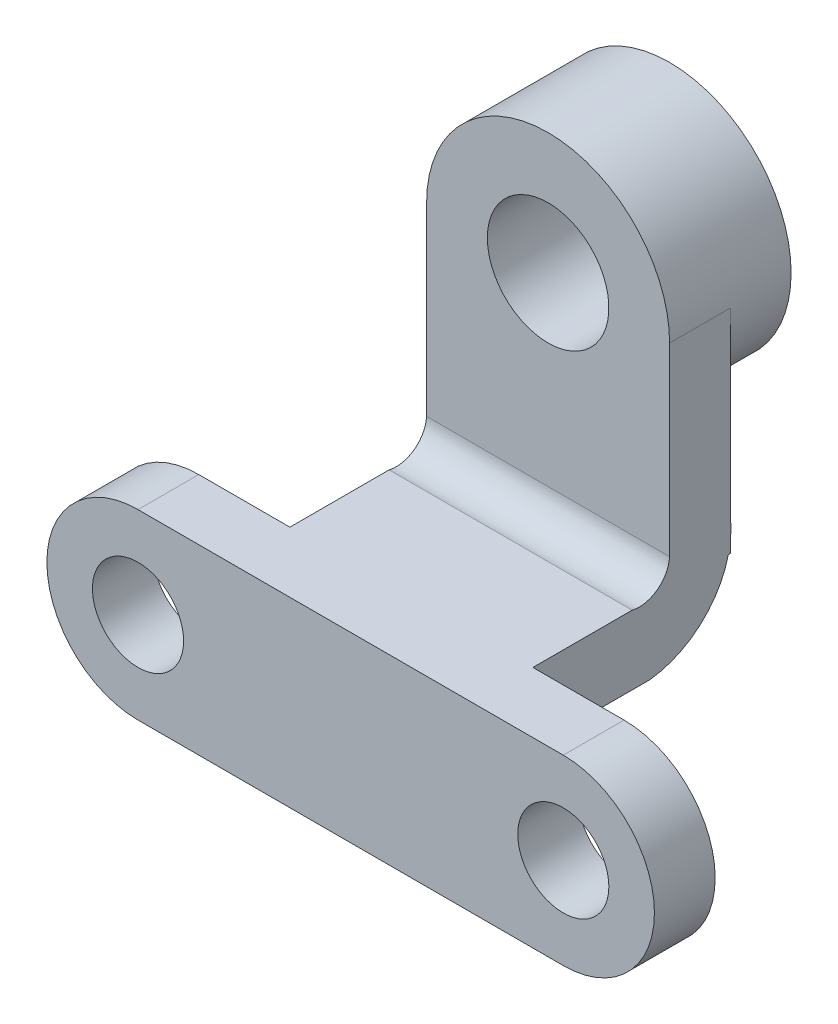
SolidWorks part; units mm, degrees
ref_plane "Front Plane" through (0, 0, 0) normal (0, 0, 1) x (1, 0, 0)
ref_plane "Top Plane" through (0, 0, 0) normal (0, 1, 0) x (1, 0, 0)
ref_plane "Right Plane" through (0, 0, 0) normal (1, 0, 0) x (0, 0, -1)
sketch "Sketch1" plane through (0, 0, 0) normal (0, 0, 1) x (1, 0, 0)
  line L0 (-78.5091, 0) -> (99.2909, 0) construction
  line L1 (-78.5091, 38.1) -> (99.2909, 38.1)
  line L2 (-78.5091, -38.1) -> (99.2909, -38.1)
  arc A0 (-78.5091, 38.1) -> (-78.5091, -38.1) centre (-78.5091, 0) ccw
  arc A1 (99.2909, -38.1) -> (99.2909, 38.1) centre (99.2909, 0) ccw
  circle A2 centre (-78.5091, 0) radius 19.05
  circle A3 centre (99.2909, 0) radius 19.05
  point P3 (10.3909, 0)
  dimension "D1" = 38.1
  dimension "D3" = 38.1
  dimension "D4" = 38.1
  dimension "D2" = 177.8
extrude "Boss-Extrude1" add sketch "Sketch1" against normal blind 25.4
ref_plane "Plane1" through (0, 0, -82.55) normal (0, 0, -1) x (-1, 0, 0)
sketch "Sketch3" plane through (0, 0, -82.55) normal (0, 0, -1) x (-1, 0, 0)
  line L0 (-61.1909, 127) -> (-61.1909, 38.1)
  line L1 (-99.2909, 38.1) -> (78.5091, 38.1) construction
  line L2 (40.4091, 127) -> (40.4091, 38.1)
  line L3 (40.4091, 38.1) -> (-61.1909, 38.1)
  arc A0 (40.4091, 127) -> (-61.1909, 127) centre (-10.3909, 127) ccw
  circle A1 centre (-10.3909, 127) radius 25.4
  circle A2 centre (78.5091, 0) radius 19.05 construction
  dimension "D1" = 101.6
  dimension "D2" = 50.8
  dimension "D3" = 127
extrude "Boss-Extrude2" add sketch "Sketch3" along normal blind 25.4 separate body
sketch "Sketch4" plane through (0, 0, -107.95) normal (0, 0, -1) x (-1, 0, 0)
  circle A0 centre (-10.3909, 127) radius 50.8
  circle A1 centre (-10.3909, 127) radius 25.4
extrude "Boss-Extrude3" add sketch "Sketch4" along normal blind 25.4
sketch "Sketch5" plane through (0, 38.1, 0) normal (0, 1, 0) x (1, 0, 0)
  line L0 (-40.1917, 82.55) -> (61.1909, 82.55)
  line L1 (41.91, 82.55) -> (-41.91, 82.55) construction
  line L2 (-40.4091, 82.55) -> (61.1909, 82.55) construction
sketch "Sketch6" plane through (61.1909, 0, 0) normal (1, 0, 0) x (0, 0, -1)
  line L0 (82.55, 127) -> (82.55, 38.1) construction
  line L3 (25.4, 38.1) -> (66.8699, 38.1)
  line L4 (107.95, 127) -> (107.95, 38.1) construction
  line L5 (74.2489, 9.2051) -> (25.4, 9.2051)
  line L6 (25.4, -38.1) -> (25.4, 38.1) construction
  line L7 (25.4, 9.2051) -> (25.4, 38.1)
  line L8 (82.55, 51.2462) -> (107.95, 51.2462)
  arc A0 (82.55, 51.2462) -> (66.8699, 38.1) centre (69.8757, 50.4392) cw
  arc A1 (107.95, 51.2462) -> (74.2489, 9.2051) centre (70.0789, 47.0762) cw
  dimension "D1" = 12.7
  dimension "D2" = 38.1
extrude "Boss-Extrude4" add sketch "Sketch6" against normal blind 101.6
